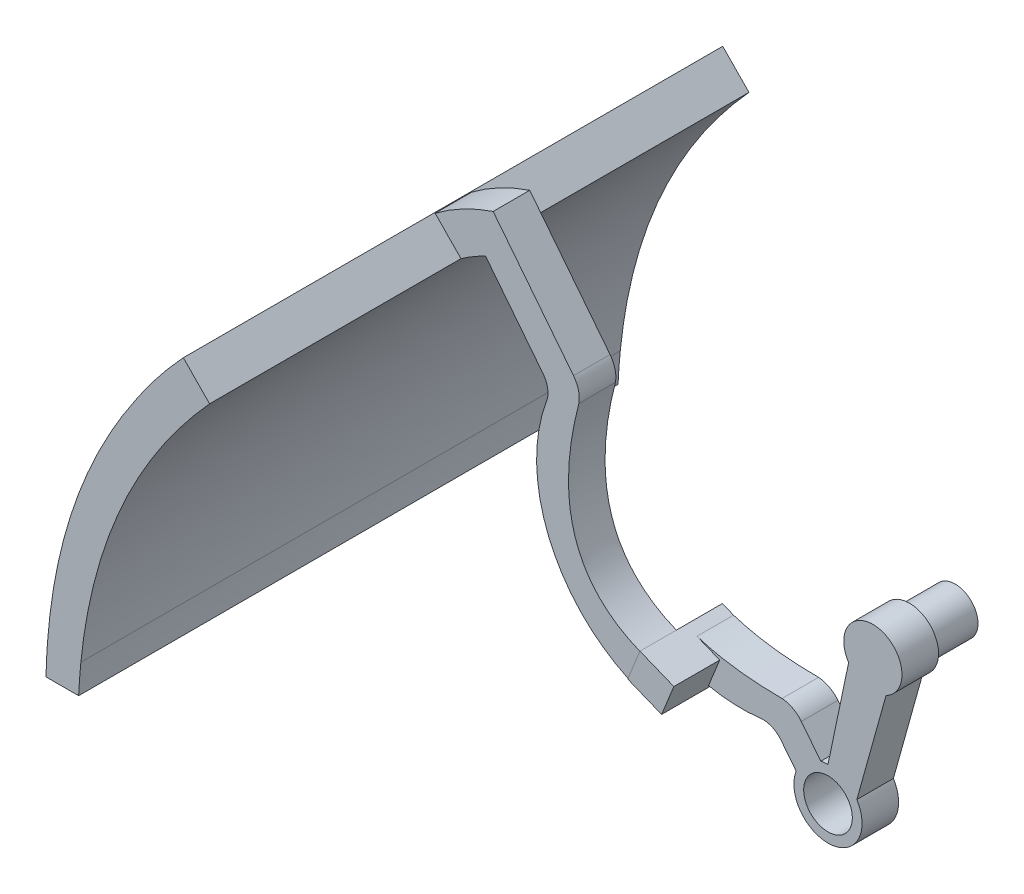
SolidWorks part; units mm, degrees
ref_plane "Front Plane" through (0, 0, 0) normal (0, 0, 1) x (1, 0, 0)
ref_plane "Top Plane" through (0, 0, 0) normal (0, 1, 0) x (1, 0, 0)
ref_plane "Right Plane" through (0, 0, 0) normal (1, 0, 0) x (0, 0, -1)
sketch "Sketch1" plane through (0, 0, 0) normal (0, 0, 1) x (1, 0, 0)
  line L4 (-16.2958, 0.6246) -> (-12.9075, 0.6246)
  line L6 (-15.8122, 3.1646) -> (-12.4433, 3.1646) construction
  line L7 (5.6776, 40.6472) -> (2.0317, 44.371) construction
  line L8 (2.0317, 44.371) -> (5.6776, 40.6472)
  line L9 (-15.8122, 3.1646) -> (-16.2958, 0.6246)
  line L10 (-12.4433, 3.1646) -> (-12.9075, 0.6246)
  line L11 (1.422, 48.6244) -> (-15.9394, 16.0823) construction
  line L12 (2.0317, 44.371) -> (-13.5164, 15.2278) construction
  line L13 (8.8419, 41.046) -> (1.422, 48.6244) construction
  line L14 (-8.3852, 11.2421) -> (8.8419, 41.046) construction
  line L15 (-10.8046, 12.1319) -> (5.6776, 40.6472) construction
  line L16 (-10.3254, 0.6246) -> (-8.3852, 11.2421) construction
  line L17 (-12.4433, 3.1646) -> (-10.8046, 12.1319) construction
  line L18 (-18.8814, 0.6246) -> (-10.3254, 0.6246) construction
  spline S1 degree 1 poles (-13.5164, 15.2278) (-15.8122, 3.1646) knots 0 0 1 1 construction
  spline S8 degree 3 poles (-15.9394, 16.0823) (-16.1844, 14.7942) (-16.6747, 12.2179) (-17.4101, 8.3535) (-17.9442, 5.5474) (-18.3138, 3.6061) (-18.559, 2.318) (-18.7605, 1.2596) (-18.8814, 0.6246) knots -0.003069 -0.003069 -0.003069 -0.003069 0.000865 0.004799 0.008732 0.009434 0.010727 0.012666 0.012666 0.012666 0.012666
  spline S12 degree 3 poles (2.0317, 44.371) (1.5451, 43.8493) (0.584, 42.7847) (-1.2279, 40.6343) (-4.2059, 36.7376) (-7.8686, 30.8427) (-11.2851, 23.2592) (-12.8911, 17.9284) (-13.5164, 15.2278) knots 0.192223 0.192223 0.192223 0.192223 0.287167 0.382111 0.572 0.951777 1.331554 1.711331 1.711331 1.711331 1.711331
  spline S13 degree 3 poles (-13.5164, 15.2278) (-13.7077, 14.2225) (-14.0902, 12.212) (-14.6641, 9.1962) (-15.2381, 6.1804) (-15.6209, 4.1699) (-15.8122, 3.1646) knots -0.002683 -0.002683 -0.002683 -0.002683 0.000387 0.003457 0.006527 0.009597 0.009597 0.009597 0.009597
  spline S14 degree 3 poles (-12.4433, 3.1646) (-12.3067, 3.9119) (-11.897, 6.1537) (-11.3508, 9.1428) (-10.9412, 11.3846) (-10.8046, 12.1319) knots 0.002076 0.002076 0.002076 0.002076 0.004355 0.008913 0.011192 0.011192 0.011192 0.011192
  spline S15 degree 3 poles (-10.8046, 12.1319) (-10.1318, 14.8139) (-8.4286, 20.0889) (-4.7699, 27.6024) (-0.8821, 33.37) (2.6966, 37.6291) (4.6636, 39.6689) (5.6776, 40.6472) knots -0.595137 -0.595137 -0.595137 -0.595137 -0.254899 0.085339 0.425577 0.595696 0.765815 0.765815 0.765815 0.765815
  dimension "D2" = 2.54
extrude "Boss-Extrude1" add sketch "Sketch1" along normal blind 74.93 contours S15 L8 S12 S13 L9 L4 L10 S14
ref_plane "Plane1" through (0, 0, 37.465) normal (0, 0, -1) x (-1, 0, 0)
sketch "Sketch4" plane through (0, 0, 37.465) normal (0, 0, -1) x (-1, 0, 0)
  line L0 (-2.0317, 44.371) -> (-5.6776, 40.6472) construction
  line L1 (-2.0317, 44.371) -> (-5.6776, 40.6472)
  line L5 (-10.1449, 48.562) -> (-12.3422, 43.9333)
  line L6 (-40.0025, 32.4269) -> (-55.4917, 2.9233) construction
  line L7 (-44.5004, 34.7882) -> (-59.9895, 5.2847) construction
  arc A0 (-5.6776, 40.6472) -> (-12.3422, 43.9333) centre (-19.2461, 21.53) ccw
  arc A1 (-2.0871, 44.3144) -> (-10.1449, 48.562) centre (-19.2461, 21.53) ccw
  arc A2 (-2.7374, 44.7899) -> (-44.5004, 34.7882) centre (-19.2461, 21.53) ccw construction
  arc A3 (-5.6776, 40.6472) -> (-40.0025, 32.4269) centre (-19.2461, 21.53) ccw construction
  dimension "D1" = 5.08
extrude "Boss-Extrude4" add sketch "Sketch4" along normal blind 2.54 and the other way blind 2.54
sketch "Sketch5" plane through (0, 0, 34.925) normal (0, 0, -1) x (-1, 0, 0)
  circle A0 centre (-9.1835, 45.3695) radius 1.4292
sketch "Sketch8" plane through (0, 0, 0) normal (0, 0, -1) x (-1, 0, 0)
  line L0 (12.2, 0.6287) -> (16.8437, 0.6287)
  line L1 (-5.6776, 40.6472) -> (-2.0317, 44.371)
  spline S0 degree 2 poles (-5.6776, 40.6472) (9.879, 23.5215) (12.2, 0.6287) knots 0 0 0 1 1 1
  spline S1 degree 2 poles (-2.0317, 44.371) (15.0089, 25.4946) (16.8437, 0.6287) knots 0 0 0 1 1 1
extrude "Boss-Extrude6" add sketch "Sketch8" against normal up to vertex (74.93 mm away) up to point (5.6776, 40.6472, 74.93)
sketch "Sketch7" plane through (0, 0, 0) normal (0, 0, -1) x (-1, 0, 0)
  circle A0 centre (14.0387, 3.7592) radius 1.25
  dimension "D1" = 2.5
sketch "Sketch9" plane through (0, 0, 74.93) normal (0, 0, 1) x (1, 0, 0)
  line L6 (5.6776, 40.6472) -> (2.0317, 44.371)
  line L7 (-16.8437, 0.6287) -> (-16.295, 0.6287)
  line L8 (-16.295, 0.6287) -> (-16.2958, 0.6246)
  line L9 (-16.2958, 0.6246) -> (-12.9075, 0.6246)
  line L10 (-12.9075, 0.6246) -> (-12.9068, 0.6287)
  line L11 (-12.9068, 0.6287) -> (-12.2, 0.6287)
  line L12 (5.6776, 40.6472) -> (2.0317, 44.371)
  line L13 (-16.8437, 0.6287) -> (-16.295, 0.6287)
  line L14 (-16.295, 0.6287) -> (-16.2958, 0.6246)
  line L15 (-16.2958, 0.6246) -> (-12.9075, 0.6246)
  line L16 (-12.9075, 0.6246) -> (-12.9068, 0.6287)
  line L17 (-12.9068, 0.6287) -> (-12.2, 0.6287)
  parabola Q2 (-12.2, 0.6287) -> (5.6776, 40.6472) focus (23.6762, 8.2321) apex (-6.8175, 21.519)
  parabola Q3 (-4.5365, 36.0597) -> (-16.8437, 0.6287) focus (20.2122, 9.2238) apex (-12.0584, 21.9349)
  parabola Q4 (-12.2, 0.6287) -> (5.6776, 40.6472) focus (23.6762, 8.2321) apex (-6.8175, 21.519)
  parabola Q5 (-4.5365, 36.0597) -> (-16.8437, 0.6287) focus (20.2122, 9.2238) apex (-12.0584, 21.9349)
  spline S1 degree 3 poles (-1957.9807, -2226.1255) (123.2572, 102.2338) (30.2091, 77.9435) (-1.2279, 40.6343) (-108.5489, -99.7905) (407.0769, -585.0968) (2829.7881, -777.2635) knots -6.017137 -6.017137 -6.017137 -6.017137 0.287167 0.382111 0.572 24.238034 24.238034 24.238034 24.238034 only from (2.0317, 44.371) to (-4.5365, 36.0597)
  spline S2 degree 3 poles (2.0317, 44.371) (1.5451, 43.8493) (0.584, 42.7847) (-1.2279, 40.6343) (-2.9419, 38.3915) (-4.1401, 36.6553) (-4.5365, 36.0597) knots 0.192223 0.192223 0.192223 0.192223 0.287167 0.382111 0.572 0.669689 0.669689 0.669689 0.669689
  dimension "D1" = 0
extrude "Cut-Extrude2" [suppressed] cut sketch "Sketch9" against normal blind 0.508
mirror "Mirror4" [suppressed] about plane through (0, 0, 37.465) normal (0, 0, -1)
sketch "Sketch10" plane through (0, 0, 74.93) normal (0, 0, 1) x (1, 0, 0)
  line L0 (-17.0442, -3.569) -> (-12.512, -3.569)
  line L1 (-16.8437, 0.6287) -> (-12.2, 0.6287)
  parabola Q0 (5.6776, 40.6472) -> (-12.2, 0.6287) focus (23.6762, 8.2321) apex (-6.8175, 21.519) construction
  parabola Q1 (-16.8437, 0.6287) -> (-4.5365, 36.0597) focus (20.2122, 9.2238) apex (-12.0584, 21.9349) construction
  parabola Q2 (-12.2, 0.6287) -> (-12.512, -3.569) focus (23.6762, 8.2321) apex (-6.8175, 21.519)
  parabola Q3 (-17.0442, -3.569) -> (-16.8437, 0.6287) focus (20.2122, 9.2238) apex (-12.0584, 21.9349)
  line M5 (-16.8437, 0.6287) -> (-16.295, 0.6287)
  line M6 (-16.295, 0.6287) -> (-16.2958, 0.6246)
  line M7 (-16.2958, 0.6246) -> (-12.9075, 0.6246)
  line M8 (-12.9075, 0.6246) -> (-12.9068, 0.6287)
  line M9 (-12.9068, 0.6287) -> (-12.2, 0.6287)
extrude "Boss-Extrude7" add sketch "Sketch10" against normal up to vertex (74.93 mm away) contours Q3 L0 Q2 M9 M8 M7 M6 M5 up to point (-16.8437, 0.6287, 0)
sketch "Sketch11" plane through (0, 0, 37.465) normal (0, 0, -1) x (-1, 0, 0)
  line L0 (-10.1449, 48.562) -> (-21.3062, 34.3875)
  line L2 (-45.8945, -4.0843) -> (-43.7666, -1.382)
  line L3 (-6.6616, 45.7399) -> (-10.1449, 48.562)
  line L7 (-49.3061, -1.1712) -> (-45.8945, -4.0843) construction
  line L9 (-46.603, 2.2615) -> (-49.3061, -1.1712)
  line L10 (-17.0798, 32.5093) -> (-6.6616, 45.7399)
  line L11 (-50.307, -5.7975) -> (-56.5408, 14.8729) construction
  line L12 (-59.3777, 14.8729) -> (-54.3155, -3.2803)
  line L13 (-53.764, 15.4541) -> (-50.307, -1.0642)
  circle A0 centre (-50.307, -5.7975) radius 58.9903 construction
  circle A1 centre (-50.307, -5.7975) radius 3.3782
  arc A2 (-49.3061, -1.1712) -> (-50.307, -1.0642) centre (-50.307, -5.7975) ccw
  arc A3 (-54.3155, -3.2803) -> (-45.8945, -4.0843) centre (-50.307, -5.7975) ccw
  arc A4 (-17.5615, 29.4393) -> (-40.8953, -0.1937) centre (-38.2727, 21.7445) cw
  arc A6 (-46.603, 2.2615) -> (-43.9212, 3.6829) centre (-43.6552, -0.0597) cw
  arc A7 (-21.3062, 34.3875) -> (-22.0524, 31.4094) centre (-18.3584, 32.0663) ccw
  arc A8 (-17.5615, 29.4393) -> (-17.0798, 32.5093) centre (-14.5853, 30.545) cw
  arc A9 (-40.8953, -0.1937) -> (-43.7666, -1.382) centre (-41.2722, -3.3462) ccw
  arc A10 (-53.764, 15.4541) -> (-59.3777, 14.8729) centre (-56.5408, 14.8729) ccw
  spline S0 degree 3 poles (-55862.0095, 81508.7882) (-420.0509, -88.2359) (-94.4508, 118.2144) (-7.6642, 35.0815) (-4.4986, 31.5222) (-0.6932, 26.4572) (220.505, -358.8831) (-4179.7865, -2781.9309) (-27054.7903, 94868.6377) knots -14.94303 -14.94303 -14.94303 -14.94303 -0.52668 -0.327365 -0.128051 0.071264 0.469894 55.544227 55.544227 55.544227 55.544227 only from (-12.4386, 39.4335) to (5.0009, 14.7184) construction
  spline S1 degree 3 poles (-12.4386, 39.4335) (-12.0211, 39.084) (-10.3869, 37.6895) (-7.6642, 35.0815) (-4.4986, 31.5222) (-0.6932, 26.4572) (2.5394, 20.8257) (4.4136, 16.3237) (5.0009, 14.7184) knots -0.592829 -0.592829 -0.592829 -0.592829 -0.52668 -0.327365 -0.128051 0.071264 0.469894 0.685568 0.685568 0.685568 0.685568
  spline S2 degree 2 poles (-43.9212, 3.6829) (-14.804, 3.6854) (-22.0524, 31.4094) knots 0 0 0 1 1 1
  point P28 (-18.2318, 31.0463)
  dimension "D1" = 6.7564
  dimension "D2" = 3.175
  dimension "D3" = 21.59
  dimension "D4" = 55
extrude "Boss-Extrude8" add sketch "Sketch11" along normal mid plane 5.08
sketch "Sketch12" plane through (0, 0, 40.005) normal (0, 0, 1) x (1, 0, 0)
  circle A0 centre (56.5408, 14.8729) radius 3.175
  arc A1 (59.3777, 14.8729) -> (53.764, 15.4541) centre (56.5408, 14.8729) ccw construction
  dimension "D1" = 6.35
extrude "Boss-Extrude9" add sketch "Sketch12" against normal blind 11.43
sketch "Sketch13" plane through (0, 0, 40.005) normal (0, 0, 1) x (1, 0, 0)
  line L0 (30.538, 5.8285) -> (28.8862, 1.7431)
  arc A0 (17.5615, 29.4393) -> (40.8953, -0.1937) centre (38.2727, 21.7445) ccw construction
  parabola Q0 (43.9212, 3.6829) -> (22.0524, 31.4094) focus (29.178, 14.9256) apex (23.7575, 10.7936) construction
ref_plane "Plane2" through (24.222, -9.7932, 0) normal (-0.9271, 0.3748, 0) x (-0.3748, -0.9271, 0)
split "Split1" trim tools "Plane2" bodies to split 120 resulting bodies 121 122
move or copy body "Body-Move/Copy1" bodies to move or copy 122 copy no translate (0, 0, -6.35) parameters "D1"=0, "D2"=0, "D3"=6.35
sketch "Sketch14" plane through (24.222, -9.7932, 0) normal (0.9271, -0.3748, 0) x (0, 0, -1)
  line L1 (-40.0289, 12.3689) -> (-28.5745, 12.3689)
  line L2 (-40.0289, 12.3689) -> (-40.0289, 16.9102)
  line L3 (-40.0289, 16.9102) -> (-28.5745, 16.9102)
  line L4 (-28.5745, 12.3689) -> (-28.5745, 16.9102)
extrude "Boss-Extrude10" add sketch "Sketch14" along normal blind 5.08
sketch "Sketch16" plane through (0, 0, 28.575) normal (0, 0, -1) x (-1, 0, 0)
  circle A0 centre (-56.5408, 14.8729) radius 4.0436
extrude "Boss-Extrude11" add sketch "Sketch16" against normal up to surface (5.08 mm away) up to face at (46.9288, -5.7975, 33.655)
